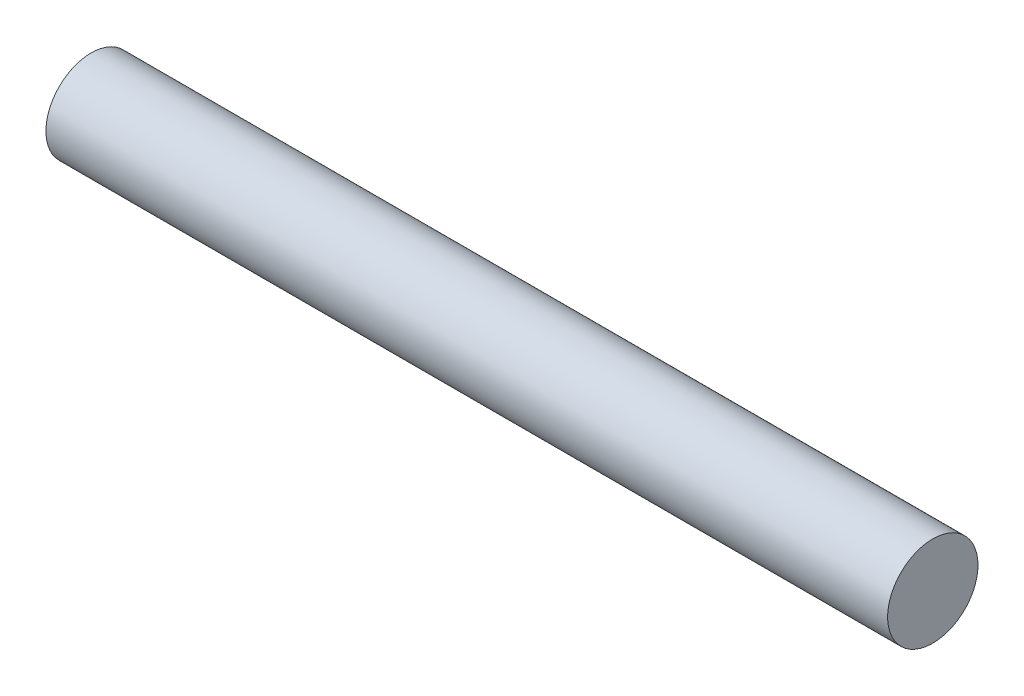
SolidWorks part; units mm, degrees
ref_plane "Спереди" through (0, 0, 0) normal (0, 0, 1) x (1, 0, 0)
ref_plane "Сверху" through (0, 0, 0) normal (0, 1, 0) x (1, 0, 0)
ref_plane "Справа" through (0, 0, 0) normal (1, 0, 0) x (0, 0, -1)
sketch "Эскиз1" plane through (0, 0, 0) normal (1, 0, 0) x (0, 0, -1)
  circle A0 centre (0, 0) radius 40
  dimension "D1" = 80
extrude "Бобышка-Вытянуть1" add sketch "Эскиз1" along normal blind 745
